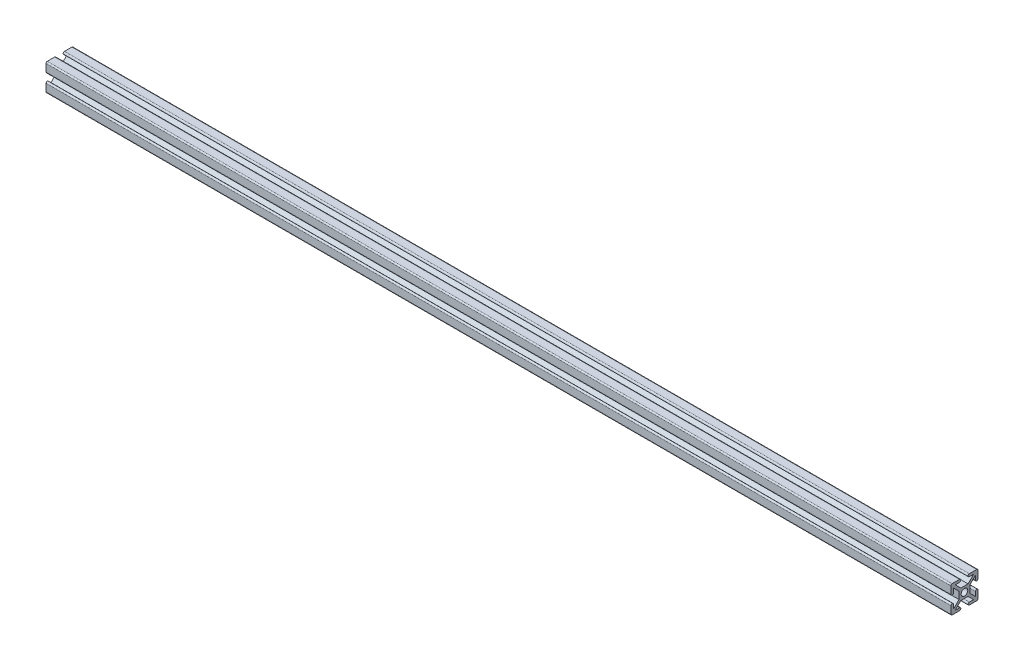
SolidWorks part; units mm, degrees
material "Aleación 6061"
ref_plane "Alzado" through (0, 0, 0) normal (0, 0, 1) x (1, 0, 0)
ref_plane "Planta" through (0, 0, 0) normal (0, 1, 0) x (1, 0, 0)
ref_plane "Vista lateral" through (0, 0, 0) normal (1, 0, 0) x (0, 0, -1)
sketch "Croquis1" plane through (0, 0, 0) normal (1, 0, 0) x (0, 0, -1)
  line L0 (-35.3044, 23.5565) -> (-35.3044, 24.9815) construction
  line L1 (-16.2515, 7.4065) -> (-11.5265, 7.4065)
  line L2 (-36.7294, 33.1315) -> (-36.7294, 24.9815)
  line L3 (-35.3044, 34.5565) -> (-27.1544, 34.5565)
  line L4 (-16.3044, 34.5565) -> (-8.1544, 34.5565)
  line L5 (-31.8265, 7.4065) -> (-27.1015, 7.4065)
  line L6 (-27.7294, 23.5565) -> (-27.7294, 15.5565)
  line L7 (-36.6765, 14.1315) -> (-36.6765, 5.9815)
  line L8 (-35.278, 4.5829) -> (-27.1015, 4.5565)
  line L9 (-6.7294, 33.1315) -> (-6.7294, 25.0852)
  line L10 (-33.8794, 29.7065) -> (-33.8794, 24.9815)
  line L11 (-6.7294, 14.2352) -> (-6.7294, 5.9815)
  line L12 (-25.7294, 33.1315) -> (-27.1544, 33.1315) construction
  line L13 (-16.2515, 4.5565) -> (-8.1544, 4.5565)
  line L14 (-31.8794, 31.7065) -> (-27.1544, 31.7065)
  line L15 (-33.8794, 14.1315) -> (-33.8794, 9.4065)
  line L16 (-17.7294, 33.1315) -> (-16.3044, 33.1315) construction
  line L17 (-16.3044, 31.7065) -> (-11.5794, 31.7065)
  line L18 (-8.1544, 23.6602) -> (-8.1544, 25.0852) construction
  line L19 (-25.7294, 25.5565) -> (-31.8794, 31.7065)
  line L20 (-9.5794, 29.7065) -> (-9.5794, 25.0852)
  line L21 (-8.1544, 15.6602) -> (-8.1544, 14.2352) construction
  line L22 (-27.7294, 23.5565) -> (-33.8794, 29.7065)
  line L23 (-9.5794, 14.2352) -> (-9.5794, 9.4065)
  line L24 (-17.6765, 5.9815) -> (-16.2515, 5.9815) construction
  line L25 (-27.7294, 15.5565) -> (-33.8794, 9.4065)
  line L26 (-25.7294, 25.5565) -> (-17.7294, 25.5565)
  line L27 (-17.7294, 25.5565) -> (-11.5794, 31.7065)
  line L28 (-35.278, 15.5565) -> (-35.278, 14.1315) construction
  line L29 (-31.8265, 7.4065) -> (-25.6765, 13.5565)
  line L30 (-25.6765, 13.5565) -> (-17.6765, 13.5565)
  line L31 (-17.6765, 13.5565) -> (-11.5265, 7.4065)
  line L32 (-25.6765, 5.9815) -> (-27.1015, 5.9815) construction
  line L33 (-15.7294, 15.5565) -> (-9.5794, 9.4065)
  line L34 (-15.7294, 23.5565) -> (-9.5794, 29.7065)
  line L35 (-15.7294, 23.5565) -> (-15.7294, 15.5565)
  circle A0 centre (-21.6765, 19.5565) radius 3.645
  arc A1 (-36.7294, 24.9815) -> (-33.8794, 24.9815) centre (-35.3044, 24.9815) ccw
  arc A2 (-27.1544, 31.7065) -> (-27.1544, 34.5565) centre (-27.1544, 33.1315) ccw
  arc A3 (-16.3044, 34.5565) -> (-16.3044, 31.7065) centre (-16.3044, 33.1315) ccw
  arc A4 (-9.5794, 25.0852) -> (-6.7294, 25.0852) centre (-8.1544, 25.0852) ccw
  arc A5 (-6.7294, 14.2352) -> (-9.5794, 14.2352) centre (-8.1544, 14.2352) ccw
  arc A6 (-16.2515, 7.4065) -> (-16.2515, 4.5565) centre (-16.2515, 5.9815) ccw
  arc A7 (-33.8794, 14.1315) -> (-36.6765, 14.1315) centre (-35.278, 14.1315) ccw
  arc A8 (-27.1015, 4.5565) -> (-27.1015, 7.4065) centre (-27.1015, 5.9815) ccw
  arc A9 (-36.6765, 5.9815) -> (-35.278, 4.5829) centre (-35.278, 5.9815) ccw
  arc A10 (-8.1544, 4.5565) -> (-6.7294, 5.9815) centre (-8.1544, 5.9815) ccw
  arc A11 (-6.7294, 33.1315) -> (-8.1544, 34.5565) centre (-8.1544, 33.1315) ccw
  arc A12 (-35.3044, 34.5565) -> (-36.7294, 33.1315) centre (-35.3044, 33.1315) ccw
  dimension "D1" = 7.29
  dimension "D2" = 1.425
  dimension "D3" = 1.425
  dimension "D4" = 1.425
  dimension "D5" = 1.425
  dimension "D6" = 1.425
  dimension "D7" = 1.425
  dimension "D8" = 1.425
  dimension "D9" = 1.425
extrude "Saliente-Extruir1" add sketch "Croquis1" along normal blind 1000
sketch "Sketch1" plane through (0, 0, 27.7294) normal (0, 0, 1) x (1, 0, 0)
  circle A0 centre (425.1, 19.5565) radius 5
  dimension "D1" = 10
extrude "Cut-Extrude1" cut sketch "Sketch1" against normal blind 12
sketch "Sketch2" plane through (0, 13.5565, 0) normal (0, -1, 0) x (1, 0, 0)
  circle A0 centre (425.1, 17.9607) radius 5
  dimension "D1" = 10
extrude "Cut-Extrude2" cut sketch "Sketch2" against normal blind 12
sketch "Sketch3" plane through (0, 0, 27.7294) normal (0, 0, 1) x (1, 0, 0)
  circle A0 centre (325, 19.5565) radius 4
  dimension "D1" = 8
extrude "Cut-Extrude3" cut sketch "Sketch3" against normal blind 12
sketch "Sketch5" plane through (0, 13.5565, 0) normal (0, -1, 0) x (1, 0, 0)
  circle A0 centre (324.3488, 21.7441) radius 4
  dimension "D1" = 8
extrude "Cut-Extrude4" cut sketch "Sketch5" against normal blind 12
